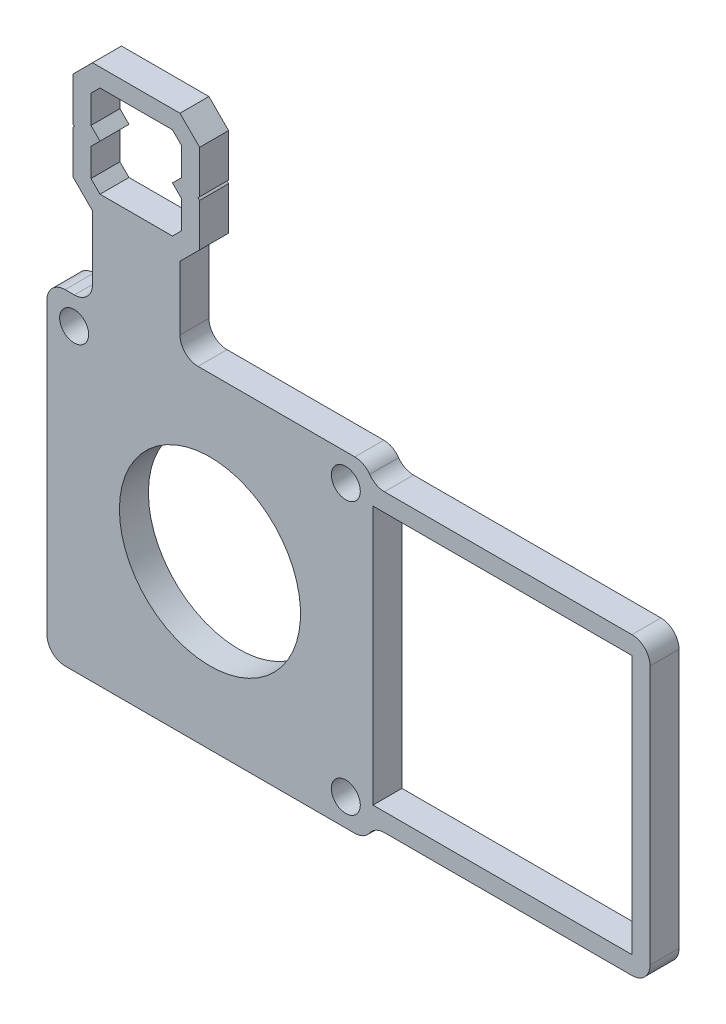
SolidWorks part; units mm, degrees
ref_plane "Front Plane" through (0, 0, 0) normal (0, 0, 1) x (1, 0, 0)
ref_plane "Top Plane" through (0, 0, 0) normal (0, 1, 0) x (1, 0, 0)
ref_plane "Right Plane" through (0, 0, 0) normal (1, 0, 0) x (0, 0, -1)
sketch "Sketch2" plane through (0, 0, -5.6) normal (0, 0, -1) x (-1, 0, 0)
  line L0 (0, 9) -> (0, -9) construction
  line L1 (-25.3, 0) -> (9, 0) construction
  line L4 (-9, -7.15) -> (-9, 7.15)
  line L5 (-23.3, -7.15) -> (-9, -7.15)
  line L6 (-23.3, 7.15) -> (-23.3, -7.15)
  line L7 (-9, 7.15) -> (-23.3, 7.15)
  line L8 (-9, -7.15) -> (-9, 7.15)
  line L9 (-23.3, -7.15) -> (-9, -7.15)
  line L10 (-23.3, 7.15) -> (-23.3, -7.15)
  line L11 (-9, 7.15) -> (-23.3, 7.15)
  line L12 (-8, -9) -> (8, -9)
  line L13 (-9, 8) -> (-9, -8)
  line L14 (8, 9) -> (-8, 9)
  line L15 (9, -8) -> (9, 8)
  line L16 (-8, -9) -> (-2, -9)
  line L17 (-9, 7.15) -> (-9, -7.15)
  line L18 (8, 9) -> (7.4854, 9)
  line L19 (9, -8) -> (9, -2)
  line L36 (-2, 9) -> (-8, 9)
  line L37 (9, 2) -> (9, 8)
  line L40 (2, -9) -> (8, -9)
  line L41 (-24.3, -8.15) -> (-9.6363, -8.15)
  line L43 (-9.6363, 8.15) -> (-24.3, 8.15)
  line L44 (-24.3, 8.15) -> (-24.3, -8.15)
  line L45 (-8, -8.15) -> (-8, 8.15) construction
  line L46 (-8, 8.15) -> (-24.3, 8.15) construction
  line L47 (-24.3, -8.15) -> (-8, -8.15) construction
  line L48 (-2, -9) -> (2, -9)
  line L49 (9, 2) -> (9, -2)
  line L50 (-2, 9) -> (0.657, 9)
  line L62 (1.5712, 16.566) -> (1.5712, 15.026)
  line L63 (2.0712, 17.066) -> (1.5712, 16.566)
  line L64 (1.5712, 17.566) -> (2.0712, 17.066)
  line L65 (1.5712, 19.106) -> (1.5712, 17.566)
  line L66 (2.0712, 19.606) -> (1.5712, 19.106)
  line L67 (6.0712, 19.606) -> (2.0712, 19.606)
  line L68 (6.5712, 19.106) -> (6.0712, 19.606)
  line L69 (6.5712, 17.566) -> (6.5712, 19.106)
  line L70 (6.0712, 17.066) -> (6.5712, 17.566)
  line L71 (6.5712, 16.566) -> (6.0712, 17.066)
  line L72 (6.5712, 15.026) -> (6.5712, 16.566)
  line L73 (6.0712, 14.526) -> (6.5712, 15.026)
  line L74 (2.0712, 14.526) -> (6.0712, 14.526)
  line L75 (1.5712, 15.026) -> (2.0712, 14.526)
  line L76 (1.5712, 16.566) -> (1.5712, 15.026)
  line L77 (2.0712, 17.066) -> (1.5712, 16.566)
  line L78 (1.5712, 17.566) -> (2.0712, 17.066)
  line L79 (1.5712, 19.106) -> (1.5712, 17.566)
  line L80 (2.0712, 19.606) -> (1.5712, 19.106)
  line L81 (6.0712, 19.606) -> (2.0712, 19.606)
  line L82 (6.5712, 19.106) -> (6.0712, 19.606)
  line L83 (6.5712, 17.566) -> (6.5712, 19.106)
  line L84 (6.0712, 17.066) -> (6.5712, 17.566)
  line L85 (6.5712, 16.566) -> (6.0712, 17.066)
  line L86 (6.5712, 15.026) -> (6.5712, 16.566)
  line L87 (6.0712, 14.526) -> (6.5712, 15.026)
  line L88 (2.0712, 14.526) -> (6.0712, 14.526)
  line L89 (1.5712, 15.026) -> (2.0712, 14.526)
  line L96 (0.5712, 16.9802) -> (0.5712, 14.6118)
  line L97 (0.5712, 14.6118) -> (1.657, 13.526)
  line L99 (6.4854, 13.526) -> (7.5712, 14.6118)
  line L100 (7.5712, 14.6118) -> (7.5712, 16.9802)
  line L101 (7.5712, 16.9802) -> (7.4854, 17.066)
  line L102 (7.4854, 17.066) -> (7.5712, 17.1518)
  line L103 (7.5712, 17.1518) -> (7.5712, 19.5202)
  line L104 (7.5712, 19.5202) -> (6.4854, 20.606)
  line L105 (6.4854, 20.606) -> (1.657, 20.606)
  line L106 (1.657, 20.606) -> (0.5712, 19.5202)
  line L107 (0.5712, 19.5202) -> (0.5712, 17.1518)
  line L108 (0.5712, 17.1518) -> (0.657, 17.066)
  line L109 (0.657, 17.066) -> (0.5712, 16.9802)
  line L110 (6.4854, 13.526) -> (6.4854, 10)
  line L111 (1.657, 13.526) -> (1.657, 10)
  line L113 (1.657, 13.526) -> (6.4854, 13.526) construction
  arc A0 (0.657, 9) -> (1.657, 10) centre (0.657, 10) ccw
  arc A2 (6.4854, 10) -> (7.4854, 9) centre (7.4854, 10) ccw
  arc A4 (8, -9) -> (9, -8) centre (8, -8) ccw
  arc A5 (-9, -8) -> (-8, -9) centre (-8, -8) ccw
  arc A6 (-8, 9) -> (-9, 8) centre (-8, 8) ccw
  arc A7 (9, 8) -> (8, 9) centre (8, 8) ccw
  arc A8 (8, -9) -> (9, -8) centre (8, -8) ccw
  arc A9 (-8.8182, -8.575) -> (-8, -9) centre (-8, -8) ccw
  arc A10 (-8, 9) -> (-8.8182, 8.575) centre (-8, 8) ccw
  arc A11 (9, 8) -> (8, 9) centre (8, 8) ccw
  arc A13 (-9.6363, 8.15) -> (-8.8182, 8.575) centre (-9.6363, 9.15) ccw
  arc A14 (-8.8182, -8.575) -> (-9.6363, -8.15) centre (-9.6363, -9.15) ccw
  circle A15 centre (0, 0) radius 5
  point P52 (0, 0)
  line M26 (-9, -7.15) -> (-9, 7.15)
  dimension "D5" = 2
  dimension "D7" = 2
  dimension "D8" = 10
  dimension "D4" = 1
  dimension "D1" = 0
  dimension "D2" = 0
  dimension "D3" = 0
  dimension "D6" = 1
extrude "Boss-Extrude1" add sketch "Sketch2" against normal blind 1.6 contours L19 A11 L18 A10 L17 A9 L16 A8 M26
sketch "Sketch4" plane through (0, 0, -5.6) normal (0, 0, -1) x (-1, 0, 0)
  circle A12 centre (-7.5, 7.5) radius 0.8
  circle A13 centre (-7.5, -7.5) radius 0.8
  circle A15 centre (7.5, 7.5) radius 0.8
  dimension "D1" = 1.6
  dimension "D2" = 1.6
  dimension "D3" = 1.6
extrude "Cut-Extrude1" cut sketch "Sketch4" against normal through all
fillet "Fillet1" radius 1 2 edges at (24.3, -8.15, -4.8) (24.3, 8.15, -4.8)
